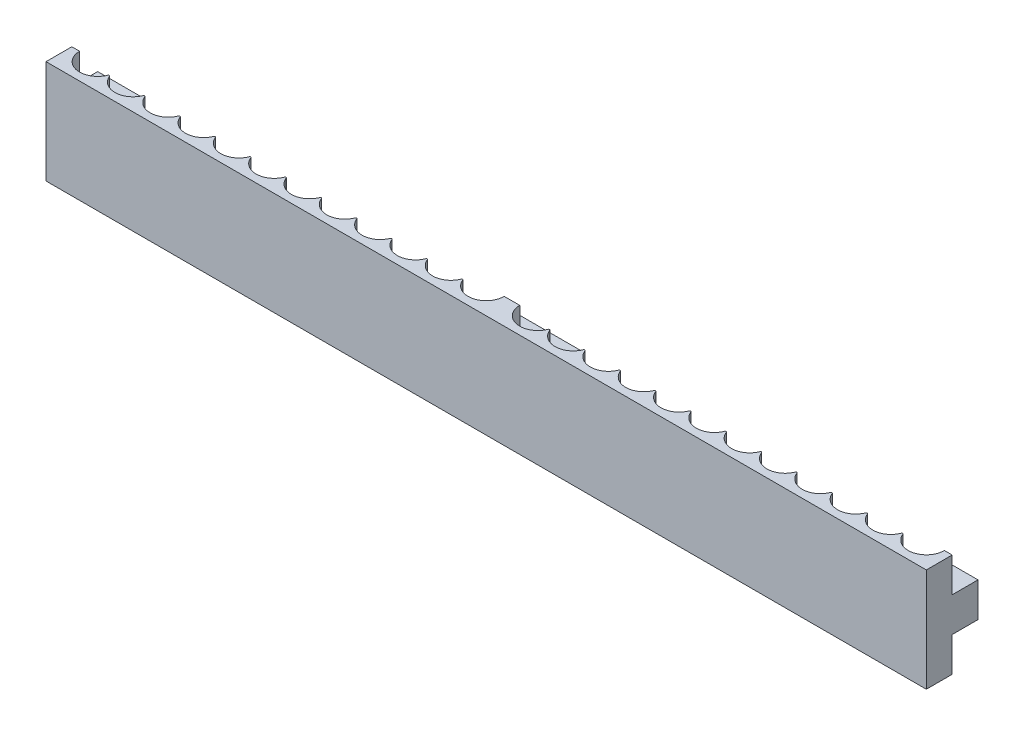
SolidWorks part; units mm, degrees
ref_plane "Front Plane" through (0, 0, 0) normal (0, 0, 1) x (1, 0, 0)
ref_plane "Top Plane" through (0, 0, 0) normal (0, 1, 0) x (1, 0, 0)
ref_plane "Right Plane" through (0, 0, 0) normal (1, 0, 0) x (0, 0, -1)
sketch "Sketch1" plane through (0, 0, 0) normal (0, 1, 0) x (1, 0, 0)
  line L0 (0, 0) -> (20.5, 0) construction
  line L10 (236, 0) -> (245, 0)
  line L11 (-15, 15) -> (496, 15) construction
  line L12 (-15, 15) -> (-15, -15) construction
  line L13 (-15, -15) -> (496, -15)
  line L20 (240.5, 15) -> (240.5, -15) construction
  line L21 (496, 15) -> (496, -15) construction
  line L22 (-15, 0) -> (-10.5, 0)
  line L23 (491.5, 0) -> (496, 0)
  line L24 (0, 0) -> (20.5, 0) construction
  line L25 (-15, 0) -> (-15, -15)
  line L26 (496, 0) -> (496, -15)
  arc A23 (9.7841, 3.8107) -> (9.7841, -3.8107) centre (0, 0) ccw
  arc A25 (10.7159, -3.8107) -> (30.2841, -3.8107) centre (20.5, 0) ccw
  arc A26 (31.2159, -3.8107) -> (50.7841, -3.8107) centre (41, 0) ccw
  arc A27 (51.7159, -3.8107) -> (71.2841, -3.8107) centre (61.5, 0) ccw
  arc A28 (72.2159, -3.8107) -> (91.7841, -3.8107) centre (82, 0) ccw
  arc A29 (92.7159, -3.8107) -> (112.2841, -3.8107) centre (102.5, 0) ccw
  arc A30 (113.2159, -3.8107) -> (132.7841, -3.8107) centre (123, 0) ccw
  arc A31 (133.7159, -3.8107) -> (153.2841, -3.8107) centre (143.5, 0) ccw
  arc A32 (154.2159, -3.8107) -> (173.7841, -3.8107) centre (164, 0) ccw
  arc A33 (174.7159, -3.8107) -> (194.2841, -3.8107) centre (184.5, 0) ccw
  arc A34 (195.2159, -3.8107) -> (214.7841, -3.8107) centre (205, 0) ccw
  arc A35 (215.7159, -3.8107) -> (215.7159, 3.8107) centre (225.5, 0) ccw
  arc A36 (30.2841, 3.8107) -> (10.7159, 3.8107) centre (20.5, 0) ccw
  arc A37 (50.7841, 3.8107) -> (31.2159, 3.8107) centre (41, 0) ccw
  arc A38 (71.2841, 3.8107) -> (51.7159, 3.8107) centre (61.5, 0) ccw
  arc A39 (91.7841, 3.8107) -> (72.2159, 3.8107) centre (82, 0) ccw
  arc A40 (112.2841, 3.8107) -> (92.7159, 3.8107) centre (102.5, 0) ccw
  arc A41 (132.7841, 3.8107) -> (113.2159, 3.8107) centre (123, 0) ccw
  arc A42 (153.2841, 3.8107) -> (133.7159, 3.8107) centre (143.5, 0) ccw
  arc A43 (173.7841, 3.8107) -> (154.2159, 3.8107) centre (164, 0) ccw
  arc A44 (194.2841, 3.8107) -> (174.7159, 3.8107) centre (184.5, 0) ccw
  arc A45 (214.7841, 3.8107) -> (195.2159, 3.8107) centre (205, 0) ccw
  arc A46 (10.7159, 3.8107) -> (9.7841, 3.8107) centre (10.25, 3.9922) cw
  arc A47 (9.7841, -3.8107) -> (10.7159, -3.8107) centre (10.25, -3.9922) cw
  arc A48 (30.2841, -3.8107) -> (31.2159, -3.8107) centre (30.75, -3.9922) cw
  arc A49 (50.7841, -3.8107) -> (51.7159, -3.8107) centre (51.25, -3.9922) cw
  arc A50 (71.2841, -3.8107) -> (72.2159, -3.8107) centre (71.75, -3.9922) cw
  arc A51 (91.7841, -3.8107) -> (92.7159, -3.8107) centre (92.25, -3.9922) cw
  arc A52 (112.2841, -3.8107) -> (113.2159, -3.8107) centre (112.75, -3.9922) cw
  arc A53 (132.7841, -3.8107) -> (133.7159, -3.8107) centre (133.25, -3.9922) cw
  arc A54 (153.2841, -3.8107) -> (154.2159, -3.8107) centre (153.75, -3.9922) cw
  arc A55 (173.7841, -3.8107) -> (174.7159, -3.8107) centre (174.25, -3.9922) cw
  arc A56 (195.2159, -3.8107) -> (194.2841, -3.8107) centre (194.75, -3.9922) ccw
  arc A57 (214.7841, -3.8107) -> (215.7159, -3.8107) centre (215.25, -3.9922) cw
  arc A58 (215.7159, 3.8107) -> (214.7841, 3.8107) centre (215.25, 3.9922) cw
  arc A59 (195.2159, 3.8107) -> (194.2841, 3.8107) centre (194.75, 3.9922) cw
  arc A60 (174.7159, 3.8107) -> (173.7841, 3.8107) centre (174.25, 3.9922) cw
  arc A61 (154.2159, 3.8107) -> (153.2841, 3.8107) centre (153.75, 3.9922) cw
  arc A62 (133.7159, 3.8107) -> (132.7841, 3.8107) centre (133.25, 3.9922) cw
  arc A63 (113.2159, 3.8107) -> (112.2841, 3.8107) centre (112.75, 3.9922) cw
  arc A64 (92.7159, 3.8107) -> (91.7841, 3.8107) centre (92.25, 3.9922) cw
  arc A65 (72.2159, 3.8107) -> (71.2841, 3.8107) centre (71.75, 3.9922) cw
  arc A66 (51.7159, 3.8107) -> (50.7841, 3.8107) centre (51.25, 3.9922) cw
  arc A67 (31.2159, 3.8107) -> (30.2841, 3.8107) centre (30.75, 3.9922) cw
  arc A68 (449.7841, 3.8107) -> (450.7159, 3.8107) centre (450.25, 3.9922) ccw
  arc A69 (429.2841, 3.8107) -> (430.2159, 3.8107) centre (429.75, 3.9922) ccw
  arc A70 (408.7841, 3.8107) -> (409.7159, 3.8107) centre (409.25, 3.9922) ccw
  arc A71 (388.2841, 3.8107) -> (389.2159, 3.8107) centre (388.75, 3.9922) ccw
  arc A72 (367.7841, 3.8107) -> (368.7159, 3.8107) centre (368.25, 3.9922) ccw
  arc A73 (347.2841, 3.8107) -> (348.2159, 3.8107) centre (347.75, 3.9922) ccw
  arc A74 (326.7841, 3.8107) -> (327.7159, 3.8107) centre (327.25, 3.9922) ccw
  arc A75 (306.2841, 3.8107) -> (307.2159, 3.8107) centre (306.75, 3.9922) ccw
  arc A76 (285.7841, 3.8107) -> (286.7159, 3.8107) centre (286.25, 3.9922) ccw
  arc A77 (265.2841, 3.8107) -> (266.2159, 3.8107) centre (265.75, 3.9922) ccw
  arc A78 (266.2159, -3.8107) -> (265.2841, -3.8107) centre (265.75, -3.9922) ccw
  arc A79 (285.7841, -3.8107) -> (286.7159, -3.8107) centre (286.25, -3.9922) cw
  arc A80 (307.2159, -3.8107) -> (306.2841, -3.8107) centre (306.75, -3.9922) ccw
  arc A81 (327.7159, -3.8107) -> (326.7841, -3.8107) centre (327.25, -3.9922) ccw
  arc A82 (348.2159, -3.8107) -> (347.2841, -3.8107) centre (347.75, -3.9922) ccw
  arc A83 (368.7159, -3.8107) -> (367.7841, -3.8107) centre (368.25, -3.9922) ccw
  arc A84 (389.2159, -3.8107) -> (388.2841, -3.8107) centre (388.75, -3.9922) ccw
  arc A85 (409.7159, -3.8107) -> (408.7841, -3.8107) centre (409.25, -3.9922) ccw
  arc A86 (430.2159, -3.8107) -> (429.2841, -3.8107) centre (429.75, -3.9922) ccw
  arc A87 (450.7159, -3.8107) -> (449.7841, -3.8107) centre (450.25, -3.9922) ccw
  arc A88 (471.2159, -3.8107) -> (470.2841, -3.8107) centre (470.75, -3.9922) ccw
  arc A89 (470.2841, 3.8107) -> (471.2159, 3.8107) centre (470.75, 3.9922) ccw
  arc A90 (266.2159, 3.8107) -> (285.7841, 3.8107) centre (276, 0) cw
  arc A91 (286.7159, 3.8107) -> (306.2841, 3.8107) centre (296.5, 0) cw
  arc A92 (307.2159, 3.8107) -> (326.7841, 3.8107) centre (317, 0) cw
  arc A93 (327.7159, 3.8107) -> (347.2841, 3.8107) centre (337.5, 0) cw
  arc A94 (348.2159, 3.8107) -> (367.7841, 3.8107) centre (358, 0) cw
  arc A95 (368.7159, 3.8107) -> (388.2841, 3.8107) centre (378.5, 0) cw
  arc A96 (389.2159, 3.8107) -> (408.7841, 3.8107) centre (399, 0) cw
  arc A97 (409.7159, 3.8107) -> (429.2841, 3.8107) centre (419.5, 0) cw
  arc A98 (430.2159, 3.8107) -> (449.7841, 3.8107) centre (440, 0) cw
  arc A99 (450.7159, 3.8107) -> (470.2841, 3.8107) centre (460.5, 0) cw
  arc A100 (265.2841, -3.8107) -> (265.2841, 3.8107) centre (255.5, 0) cw
  arc A101 (285.7841, -3.8107) -> (266.2159, -3.8107) centre (276, 0) cw
  arc A102 (306.2841, -3.8107) -> (286.7159, -3.8107) centre (296.5, 0) cw
  arc A103 (326.7841, -3.8107) -> (307.2159, -3.8107) centre (317, 0) cw
  arc A104 (347.2841, -3.8107) -> (327.7159, -3.8107) centre (337.5, 0) cw
  arc A105 (367.7841, -3.8107) -> (348.2159, -3.8107) centre (358, 0) cw
  arc A106 (388.2841, -3.8107) -> (368.7159, -3.8107) centre (378.5, 0) cw
  arc A107 (408.7841, -3.8107) -> (389.2159, -3.8107) centre (399, 0) cw
  arc A108 (429.2841, -3.8107) -> (409.7159, -3.8107) centre (419.5, 0) cw
  arc A109 (449.7841, -3.8107) -> (430.2159, -3.8107) centre (440, 0) cw
  arc A110 (470.2841, -3.8107) -> (450.7159, -3.8107) centre (460.5, 0) cw
  arc A111 (471.2159, 3.8107) -> (471.2159, -3.8107) centre (481, 0) cw
  point P62 (215.25, 2.2776)
  point P65 (194.75, 2.2776)
  point P68 (174.25, 2.2776)
  point P71 (153.75, 2.2776)
  point P74 (133.25, 2.2776)
  point P77 (112.75, 2.2776)
  point P80 (92.25, 2.2776)
  point P83 (71.75, 2.2776)
  point P86 (51.25, 2.2776)
  point P89 (30.75, 2.2776)
  point P94 (-15, 0)
  point P176 (450.25, 2.2776)
  point P177 (429.75, 2.2776)
  point P178 (409.25, 2.2776)
  point P179 (388.75, 2.2776)
  point P180 (368.25, 2.2776)
  point P181 (347.75, 2.2776)
  point P182 (327.25, 2.2776)
  point P183 (306.75, 2.2776)
  point P184 (286.25, 2.2776)
  point P185 (265.75, 2.2776)
  dimension "D1" = 21
  dimension "D2" = 12
  dimension "D7" = 15
  dimension "D4" = 0.5
  dimension "D5" = 0.5
  dimension "D3" = 20.5
  dimension "D6" = 30
  dimension "D8" = 15
extrude "Boss-Extrude5" add sketch "Sketch1" along normal mid plane 60 contours L23 A111 A88 A110 A87 A109 A86 A108 A85 A107 A84 A106 A83 A105 A82 A104 A81 A103 A80 A102 A79 A101 A78 A100 L10 A35 A57 A34 A56 A33 A55 A32 A54 A31 A53 A30 A52 A29 A51 A28 A50 A27 A49 A26 A48 A25 A47 A23 L22 L25 L13
sketch "Sketch6" plane through (0, 0, 0) normal (0, 1, 0) x (1, 0, 0)
  line L0 (496, 0) -> (496, -15) construction
  line L1 (-15, -15) -> (496, -15)
  line L2 (-15, -15) -> (-15, 15)
  line L3 (-15, 15) -> (10.5, 15)
  line L4 (496, -15) -> (496, 15)
  line L5 (10.5, 0) -> (215, 0)
  line L6 (470.5, 0) -> (470.5, 15)
  line L7 (266, 0) -> (266, 15)
  line L8 (240.5, -15) -> (240.5, 0) construction
  line L9 (10.5, 0) -> (10.5, 15)
  line L10 (215, 0) -> (215, 15)
  line L11 (215, 15) -> (266, 15)
  line L12 (470.5, 15) -> (496, 15)
  line L13 (266, 0) -> (470.5, 0)
  dimension "D1" = 30
  dimension "D2" = 15
  dimension "D3" = 25.5
  dimension "D4" = 25.5
extrude "Boss-Extrude6" add sketch "Sketch6" along normal mid plane 20
